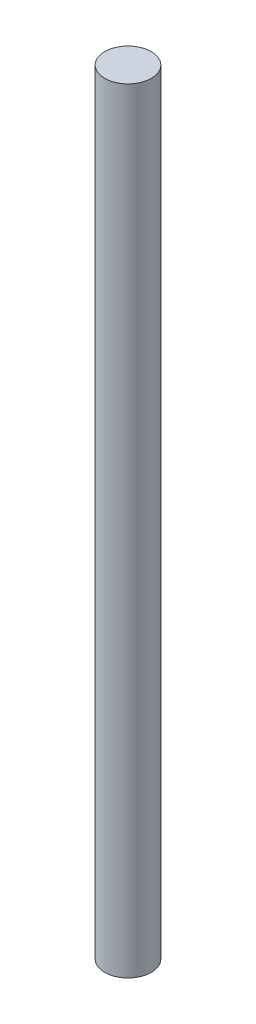
SolidWorks part; units mm, degrees
ref_plane "Front Plane" through (0, 0, 0) normal (0, 0, 1) x (1, 0, 0)
ref_plane "Top Plane" through (0, 0, 0) normal (0, 1, 0) x (1, 0, 0)
ref_plane "Right Plane" through (0, 0, 0) normal (1, 0, 0) x (0, 0, -1)
sketch "Sketch1" plane through (0, 0, 0) normal (0, 1, 0) x (1, 0, 0)
  circle A1 centre (0, 0) radius 7.5
  dimension "D1" = 15
sketch "Sketch2" plane through (0, 0, 0) normal (0, 1, 0) x (1, 0, 0)
extrude "Boss-Extrude2" add sketch "Sketch1" along normal blind 250
